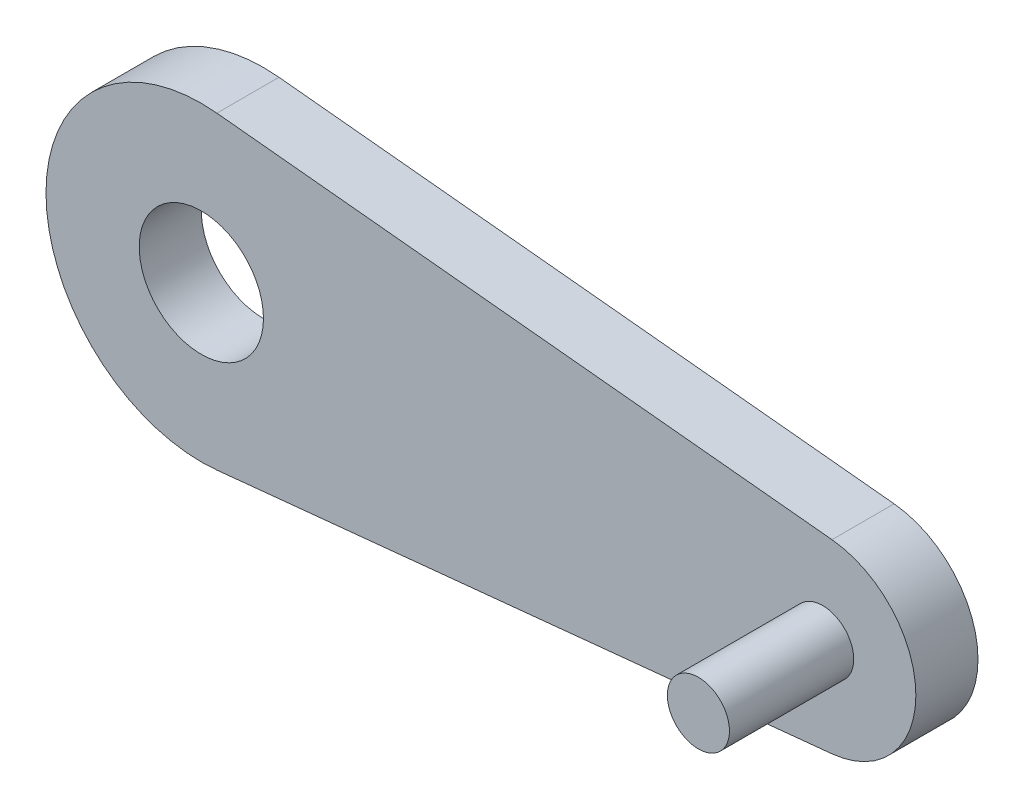
SolidWorks part; units mm, degrees
ref_plane "Front" through (0, 0, 0) normal (0, 0, 1) x (1, 0, 0)
ref_plane "Top" through (0, 0, 0) normal (0, 1, 0) x (1, 0, 0)
ref_plane "Right" through (0, 0, 0) normal (1, 0, 0) x (0, 0, -1)
sketch "草图1" plane through (0, 0, 0) normal (0, 0, 1) x (1, 0, 0)
  line L0 (-13.0215, 0) -> (14.5886, 0) construction
  line L1 (0, 11.1662) -> (0, -14.0883) construction
  line L2 (0.25, 2.4875) -> (10.15, 1.4925)
  line L3 (0.25, -2.4875) -> (10.15, -1.4925)
  circle A0 centre (0, 0) radius 1
  arc A1 (0.25, 2.4875) -> (0.25, -2.4875) centre (0, 0) ccw
  arc A2 (10.15, -1.4925) -> (10.15, 1.4925) centre (10, 0) ccw
  dimension "D1" = 10
  dimension "D2" = 3
  dimension "D3" = 5
  dimension "D4" = 2
extrude "凸台-拉伸1" add sketch "草图1" along normal blind 1
sketch "草图2" plane through (0, 0, 1) normal (0, 0, 1) x (1, 0, 0)
  circle A0 centre (10, 0) radius 0.5
extrude "凸台-拉伸2" add sketch "草图2" along normal blind 2
